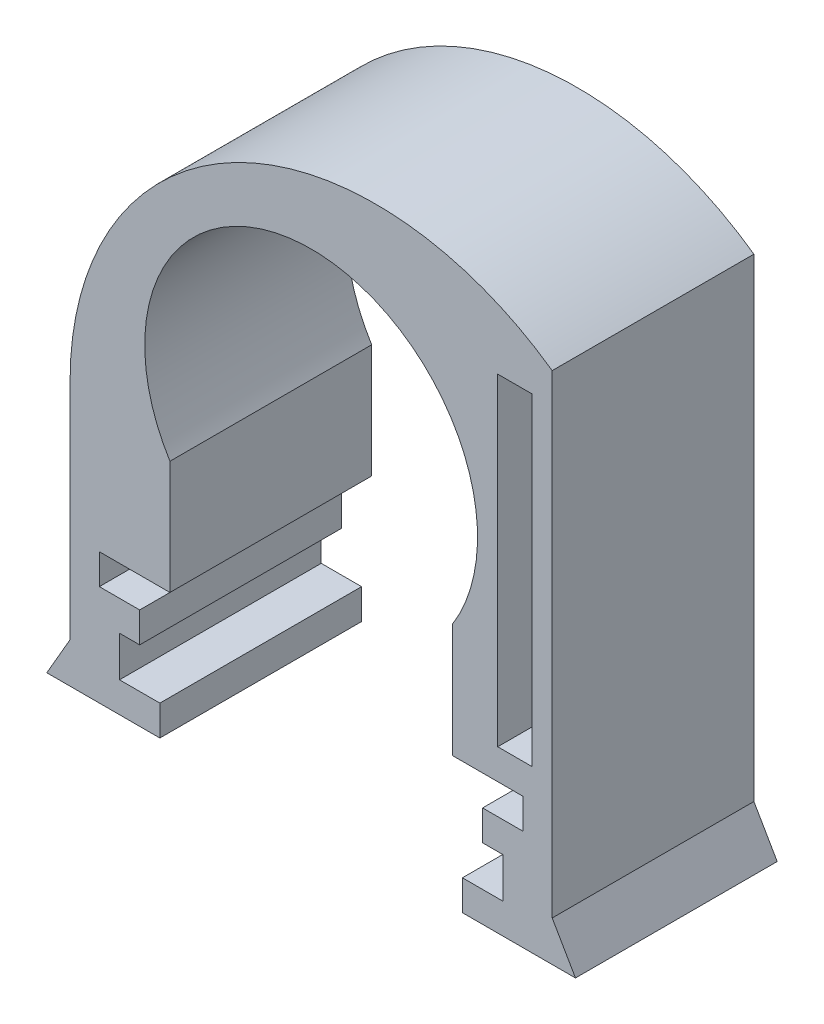
SolidWorks part; units mm, degrees
ref_plane "Front Plane" through (0, 0, 0) normal (0, 0, 1) x (1, 0, 0)
ref_plane "Top Plane" through (0, 0, 0) normal (0, 1, 0) x (1, 0, 0)
ref_plane "Right Plane" through (0, 0, 0) normal (1, 0, 0) x (0, 0, -1)
sketch "Sketch1" plane through (0, 0, 0) normal (0, 0, 1) x (1, 0, 0)
  line L0 (8.5, -13) -> (9.5, -13)
  line L1 (9.5, -13) -> (9.5, -15)
  line L2 (9.5, -15) -> (7.5, -15)
  line L3 (7.5, -15) -> (7.5, -16.5)
  line L4 (7.5, -16.5) -> (13.1047, -16.5)
  line L5 (13.1047, -16.5) -> (11.95, -14.5)
  line L6 (11.95, -14.5) -> (11.95, 9)
  line L7 (8.5, -13) -> (8.5, -11.5)
  line L8 (8.5, -11.5) -> (10.5, -11.5)
  line L9 (10.5, -11.5) -> (10.5, -10)
  line L10 (10.5, -10) -> (7, -10)
  line L11 (7, -10) -> (7, -4.3661)
  line L12 (0, 0) -> (0, -18.146) construction
  line L13 (-13.1047, -16.5) -> (-11.95, -14.5)
  line L14 (-11.95, -14.5) -> (-11.95, -3.3784)
  line L15 (-8.5, -11.5) -> (-10.5, -11.5)
  line L16 (-8.5, -13) -> (-8.5, -11.5)
  line L17 (-7.5, -16.5) -> (-13.1047, -16.5)
  line L18 (-7.5, -15) -> (-7.5, -16.5)
  line L19 (-9.5, -15) -> (-7.5, -15)
  line L20 (-9.5, -13) -> (-9.5, -15)
  line L21 (-8.5, -13) -> (-9.5, -13)
  line L22 (-10.5, -11.5) -> (-10.5, -10)
  line L23 (-10.5, -10) -> (-7, -10)
  line L24 (-7, -10) -> (-7, -4.3661)
  line L26 (9.25, 7.5) -> (10.95, 7.5)
  line L27 (9.25, 7.5) -> (9.25, -8.5)
  line L28 (9.25, -8.5) -> (10.95, -8.5)
  line L29 (10.95, 7.5) -> (10.95, -8.5)
  arc A0 (7, -4.3661) -> (-7, -4.3661) centre (0, 0) ccw
  arc A1 (11.95, 9) -> (-11.95, -3.3784) centre (3.2055, -3.3784) ccw
  dimension "D5" = 1.5
  dimension "D10" = 2
  dimension "D1" = 16.5
  dimension "D6" = 1
  dimension "D2" = 16
  dimension "D3" = 1.7
  dimension "D4" = 1.5
  dimension "D7" = 21
  dimension "D8" = 19
  dimension "D9" = 1.5
  dimension "D11" = 2
  dimension "D12" = 1
  dimension "D13" = 10
  dimension "D14" = 1.5
  dimension "D15" = 2
  dimension "D16" = 60
  dimension "D17" = 1
  dimension "D18" = 14
  dimension "D19" = 1.5
extrude "Boss-Extrude1" add sketch "Sketch1" along normal blind 10
